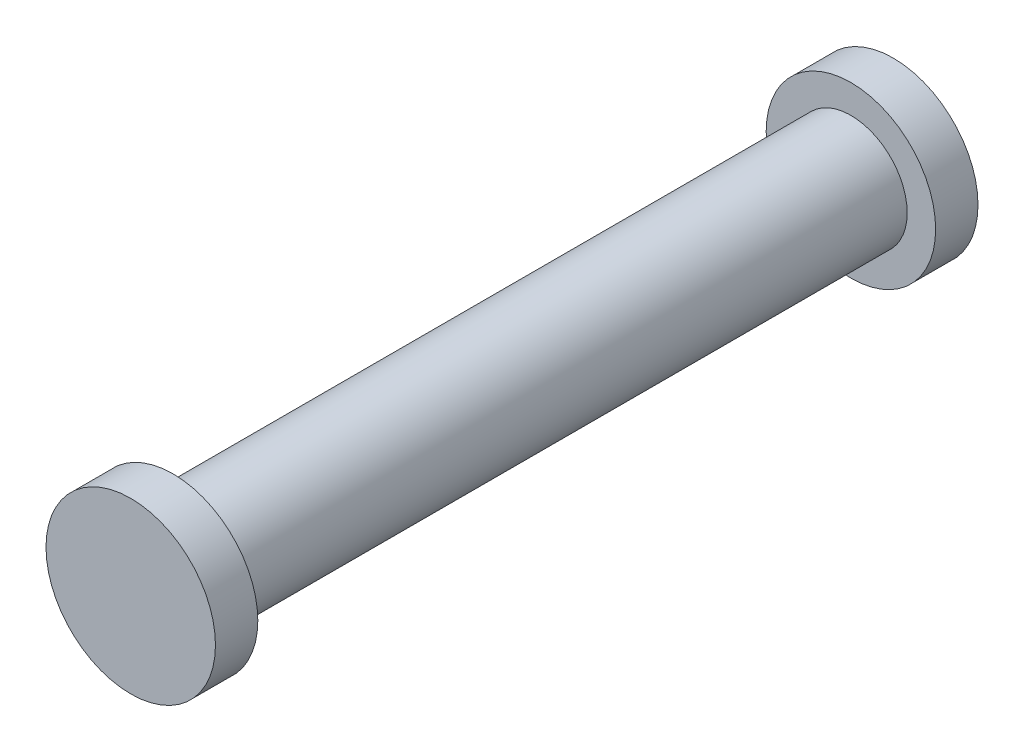
SolidWorks part; units mm, degrees
ref_plane "Front Plane" through (0, 0, 0) normal (0, 0, 1) x (1, 0, 0)
ref_plane "Top Plane" through (0, 0, 0) normal (0, 1, 0) x (1, 0, 0)
ref_plane "Right Plane" through (0, 0, 0) normal (1, 0, 0) x (0, 0, -1)
sketch "Sketch1" plane through (0, 0, 0) normal (0, 0, 1) x (1, 0, 0)
  circle A0 centre (0, 0) radius 4.2164
  dimension "D1" = 8.4328
extrude "Boss-Extrude1" add sketch "Sketch1" along normal blind 50.8 contours A0
sketch "Sketch2" plane through (0, 0, 50.8) normal (0, 0, 1) x (1, 0, 0)
  circle A0 centre (0, 0) radius 6.35
extrude "Boss-Extrude2" add sketch "Sketch2" along normal blind 3.175
sketch "Sketch3" plane through (0, 0, 0) normal (0, 0, -1) x (-1, 0, 0)
  circle A0 centre (0, 0) radius 6.35
extrude "Boss-Extrude3" add sketch "Sketch3" along normal blind 3.175
